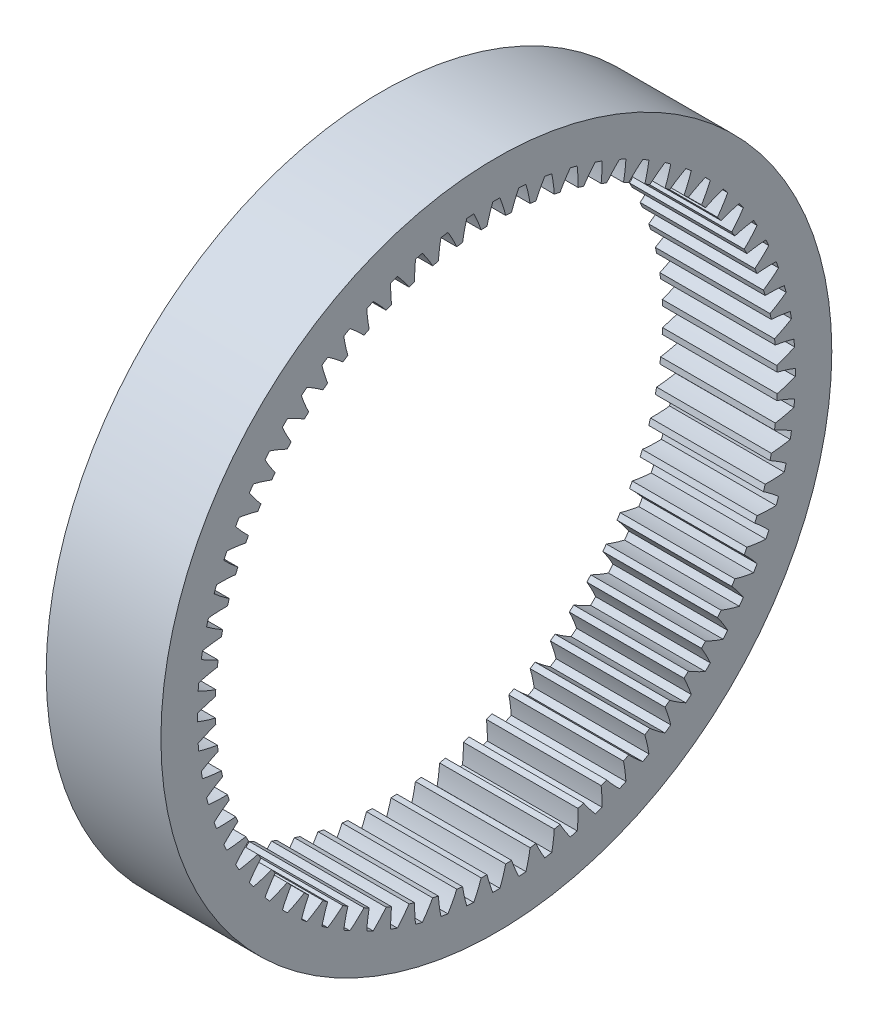
SolidWorks part; units mm, degrees
ref_plane "Plane1" through (0, 0, 0) normal (0, 0, 1) x (1, 0, 0)
ref_plane "Plane2" through (0, 0, 0) normal (0, 1, 0) x (1, 0, 0)
ref_plane "Plane3" through (0, 0, 0) normal (1, 0, 0) x (0, 0, -1)
sketch "HoldingSke" plane through (0, 0, 0) normal (0, 1, 0) x (1, 0, 0)
  line L0 (0, 0) -> (0.4415, -1.3587)
  line L1 (-15, 0) -> (100, 0) construction
  line L2 (0, 0) -> (-2.1039, 2.3779)
  line L3 (0, 0) -> (-11.863, 4.5341)
  line L4 (0, 0) -> (2.6687, 8.2133)
  line L5 (0, 0) -> (-23.7986, -8.8762)
  line L6 (0, 0) -> (-10.5278, -7.1032)
  line L7 (-2.1039, 2.3779) -> (3.3635, 27.1825)
  line L8 (-76.2, 3.0779) -> (-54.61, 3.0779)
  line L9 (-67.7845, 28.3722) -> (-49.3413, 33.142)
  line L10 (-76.2, 71.12) -> (104.1128, 71.12)
  line L11 (0, 0) -> (-10, 0)
  line L12 (-76.2, 101.6) -> (-76.173, 101.6)
  line L13 (24.9733, 27.94) -> (52.9518, 28.4284)
  line L14 (24.9733, 27.94) -> (24.9743, 27.94)
  line L15 (24.9733, 27.94) -> (100.4006, 29.5858)
  circle A0 centre (0, 0) radius 29.25
  circle A1 centre (0, 0) radius 12.7
  circle A2 centre (0, 0) radius 12.7
  dimension "MHD" = 25.4
  dimension "Hub_dia" = 25.4
  dimension "Diameter" = 58.5
  dimension "Num_teeth" = 72
  dimension "Pitch" = 1.4286
  dimension "Overall_len" = 25.4
  dimension "Show_teeth" = 72
  dimension "Thickness" = 12.7
  dimension "OAL" = 25.4001
  dimension "T_dim" = 21.59
  dimension "Ap" = 14.5
  dimension "H" = 19.05
  dimension "Pitch_radius" = 180.3128
  dimension "Width" = 10
  dimension "Backlash" = 0.027
  dimension "Addendum_fac" = 1
  dimension "Dedendum_fac" = 1.25
  dimension "Clearance_fac" = 0.25
  dimension "Dedendum_add" = 0.001
  dimension "Module" = 0.7
sketch "BasProSke" plane through (0, 0, 0) normal (0, 1, 0) x (1, 0, 0)
  line L0 (-10, 0) -> (60, 0) construction
  line L1 (0, 24.5) -> (0, 29.25)
  line L2 (0, 24.5) -> (10, 24.5)
  line L3 (10, 24.5) -> (10, 29.25)
  line L4 (10, 29.25) -> (0, 29.25)
  dimension "Diameter" = 58.5
  dimension "Thickness" = 10
  dimension "Inside_diameter" = 49
revolve "Base-Revolve" add sketch "BasProSke" angle 360 about L0
sketch "TooCutSke" plane through (0, 0, 0) normal (1, 0, 0) x (0, 0, -1)
  line L3 (0.6172, 25.1924) -> (0.6172, 53.6633) construction
  line L4 (0, 0) -> (0, 59.563) construction
  line L5 (0, 0) -> (-2.9804, 68.2625) construction
  line L6 (-11.4234, 21.4798) -> (36.849, 23.5874) construction
  circle A0 centre (0, 0) radius 25.2 construction
  circle A1 centre (0, 0) radius 26.076 construction
  circle A2 centre (0, 0) radius 21.9576 construction
  circle A3 centre (0, 0) radius 24.4746 construction
  arc A4 (0.8189, 24.4609) -> (0.3091, 26.0742) centre (-11.4234, 21.4798) ccw
  arc A5 (0.8189, 24.4609) -> (-0.8189, 24.4609) centre (0, 0) ccw
  arc A6 (0.3091, 26.0742) -> (-0.3091, 26.0742) centre (0, 0) ccw
  arc A7 (-0.3091, 26.0742) -> (-0.8189, 24.4609) centre (11.4234, 21.4798) ccw
  dimension "Pitch_dia" = 50.4
  dimension "Base_dia" = 43.9152
  dimension "Root_dia" = 52.152
  dimension "Overcut_dia" = 48.9492
  dimension "Flank_rad" = 12.6
  dimension "Half_ang" = 2.5
  dimension "Half_CT" = 0.6172
extrude "ToothCut" cut sketch "TooCutSke" along normal through all
fillet "Breaks" [suppressed] radius 0.07
fillet "RootFillets" [suppressed] radius 0.176
pattern_circular "TeethCuts" count 72 every 5 about axis through (-10, 0, 0) along (1, 0, 0) of "RootFillets", "Breaks", "ToothCut"
equation "' \"Module@HoldingSke\" = 6.35"
equation "' \"Num_teeth@HoldingSke\" = 24"
equation "' \"Ap@HoldingSke\" =  14.5"
equation "' \"Ap@HoldingSke\" = 14.5"
equation "' \"Width@HoldingSke\" = 12"
equation "' \"Diameter@HoldingSke\" = 8 * 25.4"
equation "' \"Show_teeth@HoldingSke\" = 100"
equation "' \"Backlash@HoldingSke\" = 0.009 * 25.4"
equation "' \"Addendum_fac@HoldingSke\" = 1.0"
equation "' \"Dedendum_fac@HoldingSke\" = 1.25"
equation "' \"Dedendum_add@HoldingSke\" = 0.00005 * 25.4"
equation "' \"Clearance_fac@HoldingSke\" = 0.25"
equation "\"Pitch@HoldingSke\" = 1 / \"Module@HoldingSke\" "
equation "\"Overcut_dia@TooCutSke\" = (\"Num_teeth@HoldingSke\" - 2 * \"Addendum_fac@HoldingSke\") / \"Pitch@HoldingSke\" - 0.002 * 25.4"
equation "\"Pitch_dia@TooCutSke\" = \"Num_teeth@HoldingSke\" / \"Pitch@HoldingSke\""
equation "\"Base_dia@TooCutSke\" = \"Num_teeth@HoldingSke\" / \"Pitch@HoldingSke\" * cos((\"Ap@HoldingSke\"  * 3.14159265 / 180)) * 0.90"
equation "\"Root_dia@TooCutSke\" = \"Num_teeth@HoldingSke\"  / \"Pitch@HoldingSke\" + 2 *  \"Dedendum_fac@HoldingSke\"/ \"Pitch@HoldingSke\" + \"Dedendum_add@HoldingSke\" * 2"
equation "\"Half_ang@TooCutSke\" = 180 / \"Num_teeth@HoldingSke\""
equation "\"Half_CT@TooCutSke\" = \"Num_teeth@HoldingSke\" / \"Pitch@HoldingSke\" * sin((3.14159265 / 2 / \"Num_teeth@HoldingSke\")) / 2 + 10 * \"Backlash@HoldingSke\" / 4"
equation "\"Flank_rad@TooCutSke\" = \"Num_teeth@HoldingSke\" / \"Pitch@HoldingSke\" / 4"
equation "\"Radius@RootFillets\"= \"Clearance_fac@HoldingSke\" / \"Pitch@HoldingSke\" + \"Dedendum_add@HoldingSke\""
equation "\"Break_rad@Breaks\" = 0.02 / \"Pitch@HoldingSke\" * 5"
equation "\"Num_teeth@TeethCuts\" = int( \"Show_teeth@HoldingSke\" ) + 1"
equation "\"Num_teeth@TeethCuts\" = ((sgn( \"Num_teeth@TeethCuts\" - \"Num_teeth@HoldingSke\" )-1)*( \"Num_teeth@TeethCuts\" - \"Num_teeth@HoldingSke\" ))/-2+ \"Num_teeth@HoldingSke\""
equation "\"Num_teeth@TeethCuts\" = ((sgn( \"Num_teeth@TeethCuts\" - 2.0)+1)*( \"Num_teeth@TeethCuts\" - 2.0))/2 +2.0"
equation "\"Angle@TeethCuts\" = 360.0 / \"Num_teeth@HoldingSke\""
equation "\"Diameter@BasProSke\" = \"Num_teeth@HoldingSke\"  / \"Pitch@HoldingSke\" + 2 *  \"Dedendum_fac@HoldingSke\"/ \"Pitch@HoldingSke\" + \"Dedendum_add@HoldingSke\" * 2 + 0.002 * 25.4"
equation "\"Diameter@BasProSke\" = ((sgn( \"Diameter@BasProSke\"  - \"Diameter@HoldingSke\" )+1)*( \"Diameter@BasProSke\"  - \"Diameter@HoldingSke\" ))/2 + \"Diameter@HoldingSke\""
equation "\"Inside_diameter@BasProSke\" =  (\"Num_teeth@HoldingSke\" - 2 * \"Addendum_fac@HoldingSke\") / \"Pitch@HoldingSke\" "
equation "\"Thickness@BasProSke\"= \"Width@HoldingSke\""
